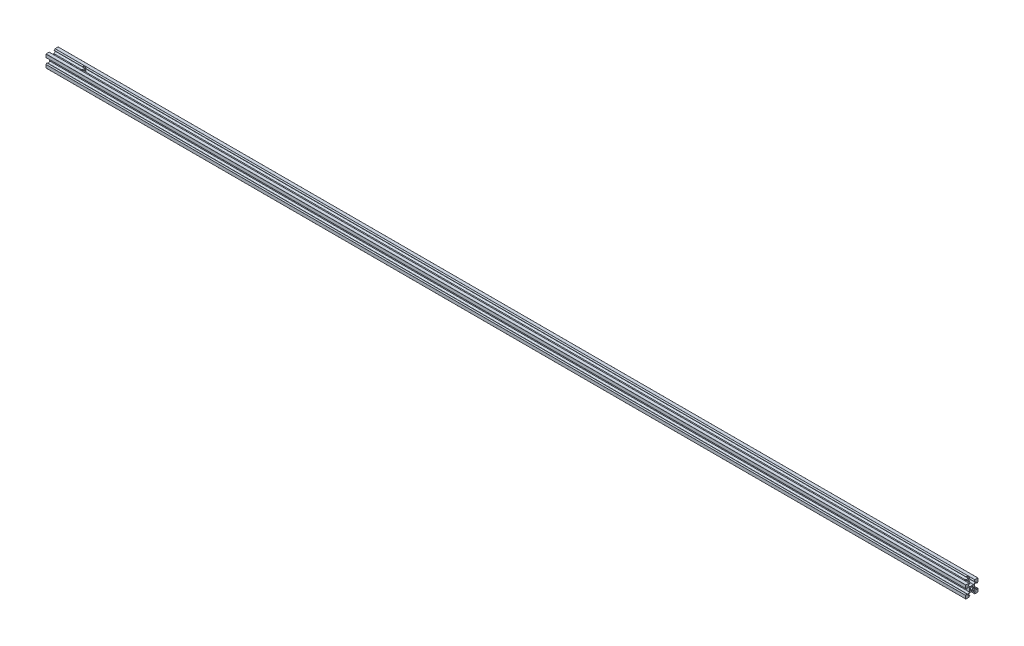
SolidWorks part; units mm, degrees
ref_plane "Front Plane" through (0, 0, 0) normal (0, 0, 1) x (1, 0, 0)
ref_plane "Top Plane" through (0, 0, 0) normal (0, 1, 0) x (1, 0, 0)
ref_plane "Right Plane" through (0, 0, 0) normal (1, 0, 0) x (0, 0, -1)
sketch "Sketch19" plane through (0, 0, 0) normal (1, 0, 0) x (0, 0, -1)
  line L0 (-4.8, 10) -> (-3.3414, 8.5414)
  line L1 (-10, 10) -> (10, 10)
  line L2 (-10, 10) -> (-10, -10)
  line L3 (-10, -10) -> (10, -10)
  line L4 (10, 10) -> (10, -10)
  line L5 (-10, 10) -> (10, -10) construction
  line L6 (-10, -10) -> (10, 10) construction
  line L8 (-3.4828, 8.2) -> (-5.2, 8.2)
  line L9 (-5.2, 8.2) -> (-5.2, 6.2)
  line L10 (-5.2, 6.2) -> (-3, 4)
  line L11 (-3, 4) -> (3, 4)
  line L12 (3, 4) -> (5.2, 6.2)
  line L13 (5.2, 6.2) -> (5.2, 8.2)
  line L14 (5.2, 8.2) -> (3.4828, 8.2)
  line L16 (3.3414, 8.5414) -> (4.8, 10)
  line L17 (4.8, 10) -> (-4.8, 10)
  line L18 (10, 4.8) -> (8.5414, 3.3414)
  line L19 (8.2, 3.4828) -> (8.2, 5.2)
  line L20 (8.2, 5.2) -> (6.2, 5.2)
  line L21 (6.2, 5.2) -> (4, 3)
  line L22 (4, 3) -> (4, -3)
  line L23 (4, -3) -> (6.2, -5.2)
  line L24 (6.2, -5.2) -> (8.2, -5.2)
  line L25 (8.2, -5.2) -> (8.2, -3.4828)
  line L26 (8.5414, -3.3414) -> (10, -4.8)
  line L27 (10, -4.8) -> (10, 4.8)
  line L28 (4.8, -10) -> (3.3414, -8.5414)
  line L29 (3.4828, -8.2) -> (5.2, -8.2)
  line L30 (5.2, -8.2) -> (5.2, -6.2)
  line L31 (5.2, -6.2) -> (3, -4)
  line L32 (3, -4) -> (-3, -4)
  line L33 (-3, -4) -> (-5.2, -6.2)
  line L34 (-5.2, -6.2) -> (-5.2, -8.2)
  line L35 (-5.2, -8.2) -> (-3.4828, -8.2)
  line L36 (-3.3414, -8.5414) -> (-4.8, -10)
  line L37 (-4.8, -10) -> (4.8, -10)
  line L38 (-10, -4.8) -> (-8.5414, -3.3414)
  line L39 (-8.2, -3.4828) -> (-8.2, -5.2)
  line L40 (-8.2, -5.2) -> (-6.2, -5.2)
  line L41 (-6.2, -5.2) -> (-4, -3)
  line L42 (-4, -3) -> (-4, 3)
  line L43 (-4, 3) -> (-6.2, 5.2)
  line L44 (-6.2, 5.2) -> (-8.2, 5.2)
  line L45 (-8.2, 5.2) -> (-8.2, 3.4828)
  line L46 (-8.5414, 3.3414) -> (-10, 4.8)
  line L47 (-10, 4.8) -> (-10, -4.8)
  arc A0 (3.4828, 8.2) -> (3.3414, 8.5414) centre (3.4828, 8.4) cw
  arc A1 (-3.3414, 8.5414) -> (-3.4828, 8.2) centre (-3.4828, 8.4) cw
  arc A2 (8.5414, 3.3414) -> (8.2, 3.4828) centre (8.4, 3.4828) cw
  arc A3 (8.2, -3.4828) -> (8.5414, -3.3414) centre (8.4, -3.4828) cw
  arc A4 (3.3414, -8.5414) -> (3.4828, -8.2) centre (3.4828, -8.4) cw
  arc A5 (-3.4828, -8.2) -> (-3.3414, -8.5414) centre (-3.4828, -8.4) cw
  arc A6 (-8.5414, -3.3414) -> (-8.2, -3.4828) centre (-8.4, -3.4828) cw
  arc A7 (-8.2, 3.4828) -> (-8.5414, 3.3414) centre (-8.4, 3.4828) cw
  point P0 (0, 0)
  point P7 (0, 4)
  point P27 (4.3414, 8.2)
  point P67 (0, 0)
  dimension "D10" = 0.2
  dimension "D1" = 20
  dimension "D2" = 20
  dimension "D3" = 2
  dimension "D4" = 45
  dimension "D5" = 6
  dimension "D6" = 1.8
  dimension "D7" = 4.2
  dimension "D8" = 9.6
  dimension "D9" = 135
  dimension "D11" = 4
extrude "Boss-Extrude3" add sketch "Sketch19" along normal blind 1500 separate body contours A7 L45 L44 L43 L42 L41 L40 L39 A6 L38 L2 L3 L36 A5 L35 L34 L33 L32 L31 L30 L29 A4 L28 L4 L26 A3 L25 L24 L23 L22 L21 L20 L19 A2 L18 L1 L16 A0 L14 L13 L12 L11 L10 L9 L8 A1 L0
sketch "Sketch20" plane through (1500, 0, 0) normal (1, 0, 0) x (0, 0, -1)
  circle A0 centre (0, 0) radius 2
  dimension "D1" = 4
extrude "Cut-Extrude5" cut sketch "Sketch20" against normal through all
chamfer "Chamfer1" distance 0.5 angle 45 2 edges at (1500, 0, -2) (0, 0, -2)
sketch "Sketch15" plane through (0, 4, 0) normal (0, 1, 0) x (-1, 0, 0)
  line L0 (0, 0) -> (-1500, 0) construction
  line L1 (-750, 0) -> (-750, -47.0667) construction
  line L2 (-1500, 2) -> (-1500, -2) construction
fillet "Fillet2" radius 0.2 12 edges at (750, 10, -10) (750, 10, -4.8) (750, 4.8, -10) (750, -4.8, -10) (750, -10, -10) (750, -10, -4.8) (750, -10, 4.8) (750, -10, 10) (750, 10, 4.8) (750, 4.8, 10) (750, 10, 10) (750, -4.8, 10)
sketch "Sketch21" plane through (0, 4, 0) normal (0, 1, 0) x (1, 0, 0)
  line L0 (0, 0) -> (1500, 0) construction
  line L1 (0, -3) -> (0, 3) construction
  circle A0 centre (3, 0) radius 1.65
  circle A1 centre (29, 0) radius 1.65
  dimension "D1" = 3.3
  dimension "D2" = 3
  dimension "D3" = 26
extrude "Cut-Extrude6" cut sketch "Sketch21" against normal up to surface (8 mm away) up to face at (750, -4, 0)
sketch "Sketch23" plane through (0, 4, 0) normal (0, 1, 0) x (1, 0, 0)
  line L1 (0, 0) -> (1500, 0) construction
  circle A1 centre (49, 0) radius 2.25
  circle A2 centre (29, 0) radius 1.65 construction
  circle A3 centre (1490, 0) radius 2.25
  dimension "D1" = 4.5
  dimension "D2" = 20
  dimension "D3" = 4.5
  dimension "D4" = 10
extrude "Cut-Extrude7" cut sketch "Sketch23" against normal through all both and the other way through all
sketch "Sketch25" plane through (0, 10, 0) normal (0, 1, 0) x (1, 0, 0)
  circle A1 centre (49, 0) radius 4.5
  circle A2 centre (1490, 0) radius 4.5
  dimension "D1" = 9
  dimension "D2" = 9
extrude "Cut-Extrude8" cut sketch "Sketch25" against normal offset from surface (7 mm away) 1 contours A2 | A1 up to face at (49, 4, 2.25) offset beyond the face yes
